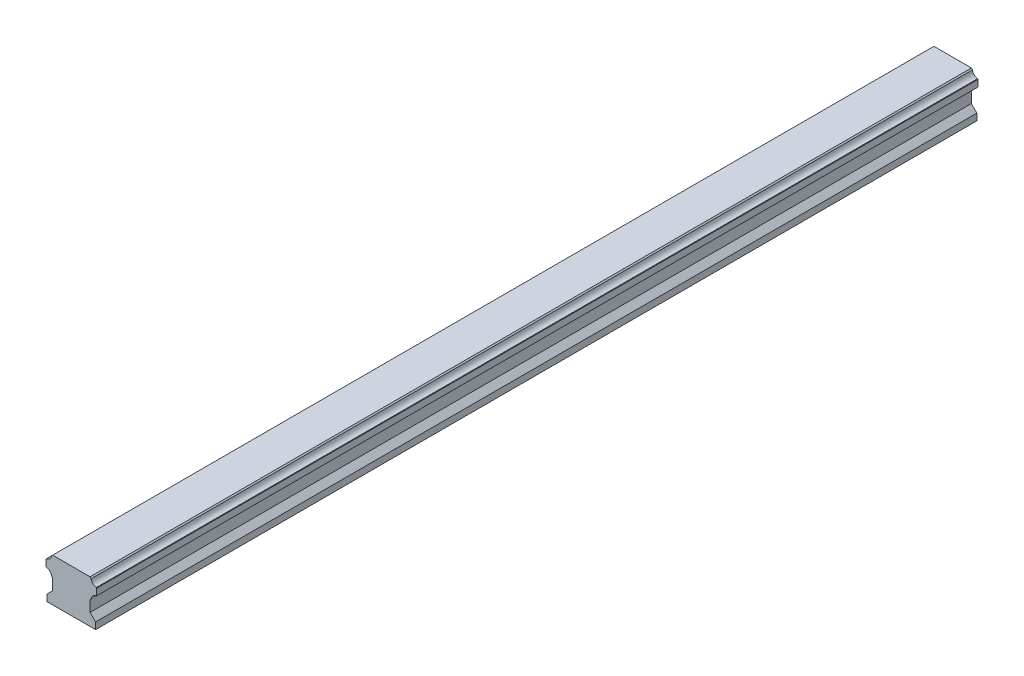
SolidWorks part; units mm, degrees
ref_plane "Piano frontale" through (0, 0, 0) normal (0, 0, 1) x (1, 0, 0)
ref_plane "Piano superiore" through (0, 0, 0) normal (0, 1, 0) x (1, 0, 0)
ref_plane "Piano destro" through (0, 0, 0) normal (1, 0, 0) x (0, 0, -1)
sketch "Schizzo1" plane through (0, 0, 0) normal (0, 0, 1) x (1, 0, 0)
  line L0 (-10.0012, -16.2762) -> (-7.5012, -13.7762)
  line L1 (-7.5012, -13.7762) -> (-7.5012, -8.7762)
  line L2 (-7.5012, -8.7762) -> (-8.0088, -8.2686)
  line L3 (-10.3066, -5.9708) -> (-10.5012, -5.7762)
  line L4 (-10.5012, -5.7762) -> (-10.5012, -2.7762)
  line L5 (-10.5012, -2.7762) -> (-10.3066, -2.5816)
  line L6 (-8.0088, -0.2838) -> (-7.5012, 0.2238)
  line L7 (-7.5012, 0.2238) -> (9.4988, 0.2238)
  line L8 (9.4988, 0.2238) -> (10.0064, -0.2838)
  line L9 (12.3042, -2.5816) -> (12.4988, -2.7762)
  line L10 (12.4988, -2.7762) -> (12.4988, -5.7762)
  line L11 (12.4988, -5.7762) -> (12.3042, -5.9708)
  line L12 (10.0064, -8.2686) -> (9.4988, -8.7762)
  line L13 (9.4988, -8.7762) -> (9.4988, -13.7762)
  line L14 (9.4988, -13.7762) -> (11.9988, -16.2762)
  line L17 (-10.0012, -16.2762) -> (-10.0012, -19.3144)
  line L18 (-10.0012, -19.3144) -> (11.9988, -19.3144)
  line L19 (11.9988, -19.3144) -> (11.9988, -16.2762)
  arc A0 (-8.0088, -8.2686) -> (-10.3066, -5.9708) centre (-10.5012, -8.4632) ccw
  arc A1 (-10.3066, -2.5816) -> (-8.0088, -0.2838) centre (-10.5012, -0.0892) ccw
  arc A2 (10.0064, -0.2838) -> (12.3042, -2.5816) centre (12.4988, -0.0892) ccw
  arc A3 (12.3042, -5.9708) -> (10.0064, -8.2686) centre (12.4988, -8.4632) ccw
extrude "Estrusione-Estrusione1" add sketch "Schizzo1" along normal blind 400
